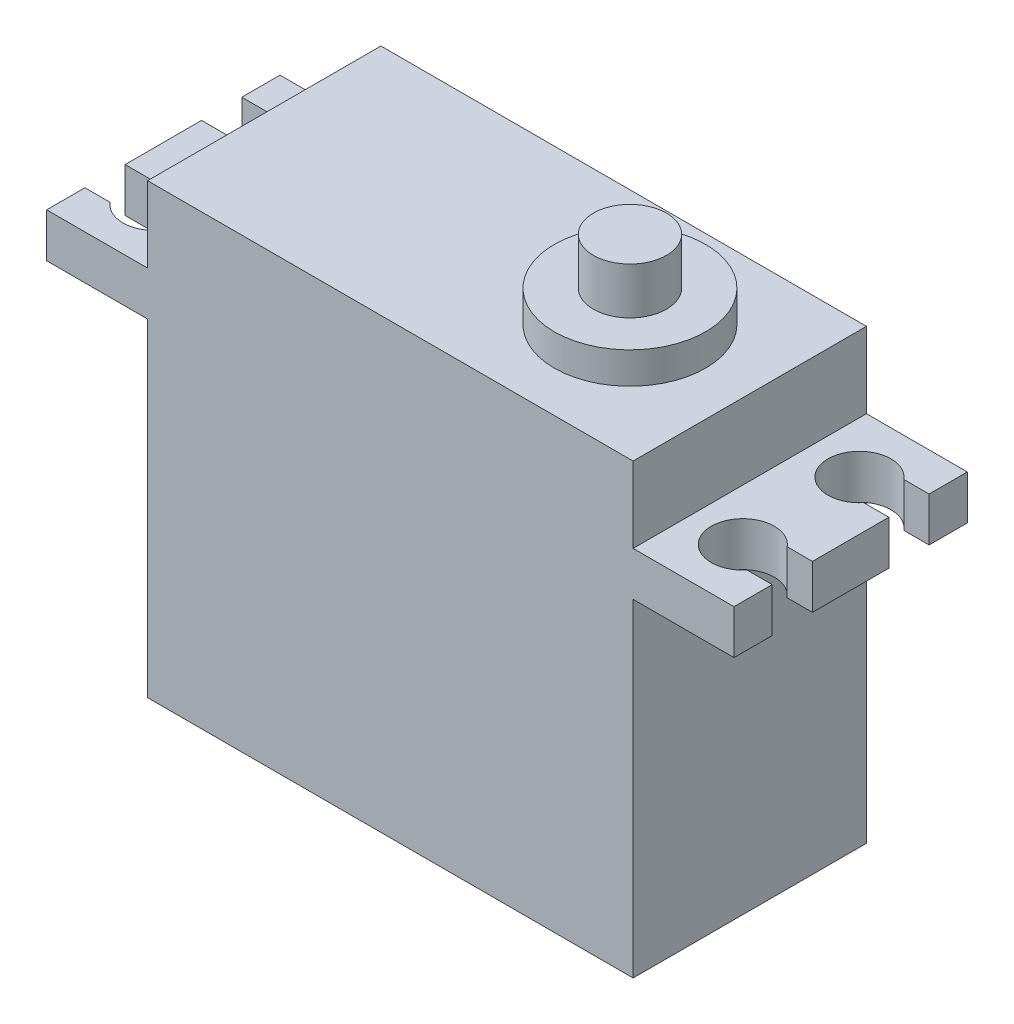
SolidWorks part; units mm, degrees
ref_plane "Plan de face" through (0, 0, 0) normal (0, 0, 1) x (1, 0, 0)
ref_plane "Plan de dessus" through (0, 0, 0) normal (0, 1, 0) x (1, 0, 0)
ref_plane "Plan de droite" through (0, 0, 0) normal (1, 0, 0) x (0, 0, -1)
sketch "Esquisse2" plane through (0, 0, 0) normal (0, 0, 1) x (1, 0, 0)
  line L0 (-9.3498, -0.1256) -> (-9.3498, 3.3744)
  line L12 (45.1502, 3.3744) -> (45.1502, -0.1256)
  line L13 (45.1502, -0.1256) -> (37.1502, -0.1256)
  line L14 (37.1502, -0.1256) -> (37.1502, -26.1256)
  line L15 (37.1502, -26.1256) -> (-1.3498, -26.1256)
  line L16 (-1.3498, -26.1256) -> (-1.3498, -0.1256)
  line L17 (-1.3498, -0.1256) -> (-9.3498, -0.1256)
  line L19 (-9.3498, 3.3744) -> (45.1502, 3.3744)
  dimension "D1" = 38.5
  dimension "D2" = 26
  dimension "D3" = 3.5
  dimension "D4" = 8
extrude "Boss.-Extru.1" add sketch "Esquisse2" along normal blind 18.5
sketch "Esquisse3" plane through (0, 3.3744, 0) normal (0, 1, 0) x (1, 0, 0)
  line L0 (-9.3498, -15.4683) -> (-7.3498, -15.4683)
  line L1 (-9.3498, -18.5) -> (-9.3498, 0) construction
  line L2 (-9.3498, -12.2817) -> (-7.3498, -12.2817)
  line L3 (-9.3498, -18.5) -> (-9.3498, -9.25) construction
  line L4 (-9.3498, -12.2817) -> (-9.3498, -15.4683) construction
  line L5 (-7.3498, -15.4683) -> (-7.3498, -12.2817) construction
  line L6 (-9.3498, -13.875) -> (-5.4233, -13.875) construction
  line L7 (-9.3498, -9.25) -> (45.1502, -9.25) construction
  line L8 (45.1502, -18.5) -> (45.1502, 0) construction
  line L9 (17.9002, -18.5) -> (17.9002, 0) construction
  line L10 (45.1502, -18.5) -> (-9.3498, -18.5) construction
  line L11 (45.1502, 0) -> (-9.3498, 0) construction
  line L12 (45.1502, -12.2817) -> (43.1502, -12.2817)
  line L13 (45.1502, -15.4683) -> (43.1502, -15.4683)
  line L14 (-9.3498, -6.2183) -> (-7.3498, -6.2183)
  line L15 (-9.3498, -3.0317) -> (-7.3498, -3.0317)
  line L16 (45.1502, -3.0317) -> (43.1502, -3.0317)
  line L17 (45.1502, -6.2183) -> (43.1502, -6.2183)
  line L18 (45.1502, -15.4683) -> (45.1502, -12.2817)
  line L19 (45.1502, -6.2183) -> (45.1502, -3.0317)
  line L20 (-9.3498, -6.2183) -> (-9.3498, -3.0317)
  line L21 (-9.3498, -12.2817) -> (-9.3498, -15.4683)
  arc A0 (-7.3498, -12.2817) -> (-7.3498, -15.4683) centre (-5.4233, -13.875) cw
  arc A1 (43.1502, -12.2817) -> (43.1502, -15.4683) centre (41.2237, -13.875) ccw
  arc A2 (43.1502, -6.2183) -> (43.1502, -3.0317) centre (41.2237, -4.625) cw
  arc A3 (-7.3498, -6.2183) -> (-7.3498, -3.0317) centre (-5.4233, -4.625) ccw
  dimension "D2" = 2.5
  dimension "D1" = 2
extrude "Enlèv. mat.-Extru.1" cut sketch "Esquisse3" against normal through all
sketch "Esquisse4" plane through (0, 3.3744, 0) normal (0, 1, 0) x (1, 0, 0)
  line L4 (37.1502, 0) -> (-1.3498, 0)
  line L5 (37.1502, -18.5) -> (37.1502, 0)
  line L6 (-1.3498, -18.5) -> (37.1502, -18.5)
  line L7 (-1.3498, 0) -> (-1.3498, -18.5)
  line L8 (37.1502, 0) -> (-1.3498, 0)
  line L9 (37.1502, -18.5) -> (37.1502, 0)
  line L10 (-1.3498, -18.5) -> (37.1502, -18.5)
  line L11 (-1.3498, 0) -> (-1.3498, -18.5)
  dimension "D1" = 0
extrude "Boss.-Extru.2" add sketch "Esquisse4" along normal blind 6
sketch "Esquisse6" plane through (0, 9.3744, 0) normal (0, 1, 0) x (1, 0, 0)
  line L0 (27.6502, -18.5) -> (27.6502, 0) construction
  line L1 (-1.3498, -18.5) -> (37.1502, -18.5) construction
  line L2 (37.1502, 0) -> (-1.3498, 0) construction
  circle A0 centre (27.6502, -9.25) radius 6
  dimension "D1" = 12
  dimension "D2" = 9.5
extrude "Boss.-Extru.3" add sketch "Esquisse6" along normal blind 2.5 contours A0
sketch "Esquisse7" plane through (0, 11.8744, 0) normal (0, 1, 0) x (1, 0, 0)
  circle A0 centre (27.6502, -9.25) radius 2.9
  circle A1 centre (27.6502, -9.25) radius 6 construction
  circle A2 centre (27.6502, -9.25) radius 6
  point P5 (0, 0)
  dimension "D1" = 5.8
extrude "Boss.-Extru.4" add sketch "Esquisse7" along normal blind 3.7 contours A0
